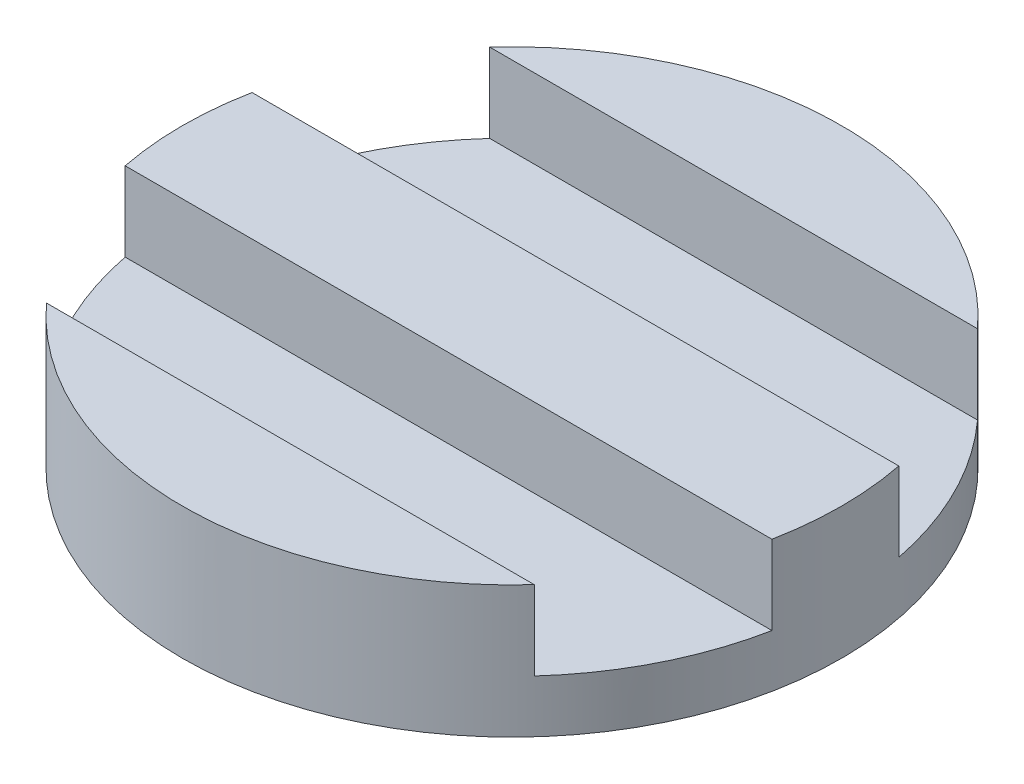
SolidWorks part; units mm, degrees
ref_plane "Front Plane" through (0, 0, 0) normal (0, 0, 1) x (1, 0, 0)
ref_plane "Top Plane" through (0, 0, 0) normal (0, 1, 0) x (1, 0, 0)
ref_plane "Right Plane" through (0, 0, 0) normal (1, 0, 0) x (0, 0, -1)
sketch "Sketch2" plane through (0, 0, 0) normal (0, 1, 0) x (1, 0, 0)
  circle A0 centre (0, 0) radius 125
  dimension "D1" = 250
extrude "Boss-Extrude1" add sketch "Sketch2" along normal blind 50
sketch "Sketch3" plane through (0, 50, 0) normal (0, 1, 0) x (1, 0, 0)
  line L0 (-122.6626, 24.06) -> (122.6626, 24.06)
  line L1 (-122.6626, -24.06) -> (122.6626, -24.06)
  line L2 (-92.5144, 84.06) -> (92.5144, 84.06)
  line L3 (-92.5144, -84.06) -> (92.5144, -84.06)
  circle A0 centre (0, 0) radius 125 construction
  arc A1 (-92.5144, 84.06) -> (-122.6626, 24.06) centre (0, 0) ccw
  arc A2 (-122.6626, -24.06) -> (-92.5144, -84.06) centre (0, 0) ccw
  arc A3 (122.6626, 24.06) -> (92.5144, 84.06) centre (0, 0) ccw
  arc A4 (92.5144, -84.06) -> (122.6626, -24.06) centre (0, 0) ccw
  dimension "D1" = 48.12
  dimension "D2" = 24.06
  dimension "D3" = 60
  dimension "D4" = 60
extrude "Cut-Extrude1" cut sketch "Sketch3" against normal blind 30
